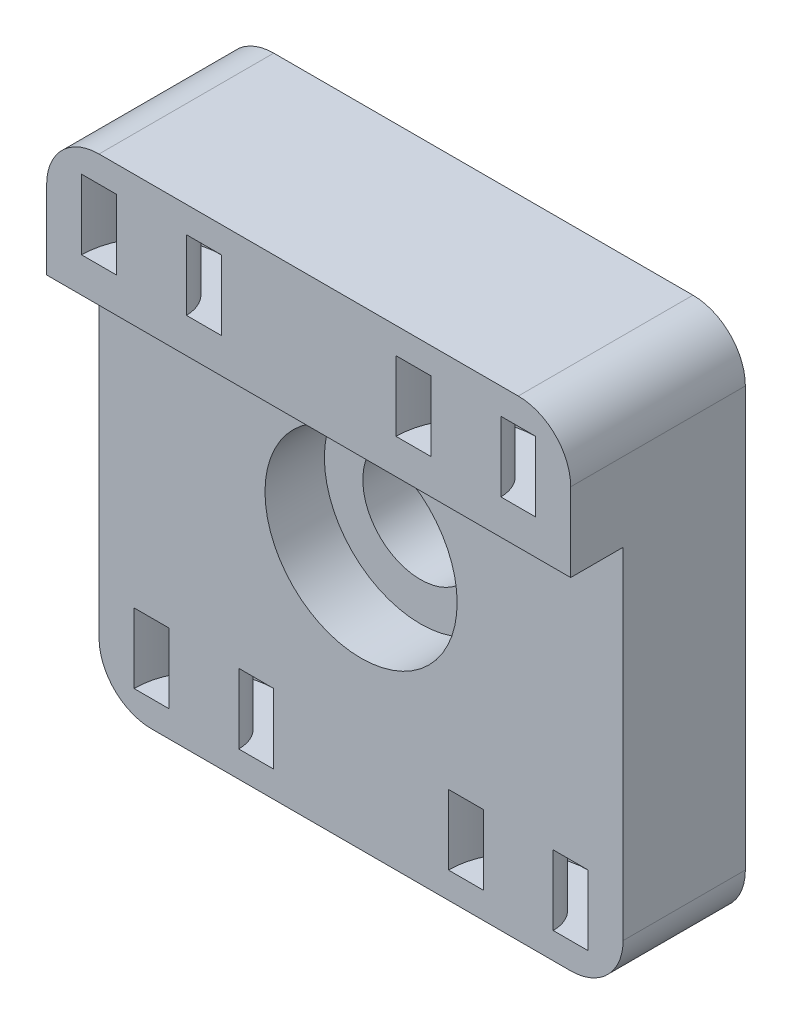
SolidWorks part; units mm, degrees
ref_plane "Přední rovina" through (0, 0, 0) normal (0, 0, 1) x (1, 0, 0)
ref_plane "Horní rovina" through (0, 0, 0) normal (0, 1, 0) x (1, 0, 0)
ref_plane "Pravá rovina" through (0, 0, 0) normal (1, 0, 0) x (0, 0, -1)
sketch "Base sketch" plane through (0, 0, 0) normal (0, 0, 1) x (1, 0, 0)
  line L1 (-15, 15) -> (15, 15)
  line L2 (-15, 15) -> (-15, -15)
  line L3 (-15, -15) -> (15, -15)
  line L4 (15, 15) -> (15, -15)
  line L5 (-15, 15) -> (15, -15) construction
  line L6 (-15, -15) -> (15, 15) construction
  point P0 (0, 0)
  dimension "D1" = 30
extrude "Base" add sketch "Base sketch" along normal blind 7
sketch "Higher adapter sketch" plane through (0, 0, 7) normal (0, 0, 1) x (1, 0, 0)
  line L0 (15, -15) -> (15, 15) construction
  line L1 (-15, 15) -> (15, 15)
  line L2 (-15, 15) -> (-15, 7.5)
  line L3 (-15, 7.5) -> (15, 7.5)
  line L4 (15, 15) -> (15, 7.5)
  dimension "D1" = 7.5
extrude "Higher adapter" add sketch "Higher adapter sketch" along normal blind 3
sketch "Mount screw sketch" plane through (0, 0, 7) normal (0, 0, 1) x (1, 0, 0)
  point P0 (0, 0)
hole_wizard "Mount screw" positions "Skica4" profile "Skica5" counterbore size "M6" standard "ISO" end condition up to next
sketch "Skica4" plane through (0, 0, 7) normal (0, 0, 1) x (1, 0, 0)
  point P0 (0, 0)
sketch "Skica5" plane through (0, 0, 7) normal (1, 0, 0) x (0, -1, 0)
  line L0 (0, 0) -> (0, 7)
  line L1 (0, 7) -> (3.3, 7)
  line L3 (3.3, 7) -> (3.3, 3.4)
  line L4 (3.3, 3.4) -> (5.5, 3.4)
  line L5 (5.5, 3.4) -> (5.5, 0)
  line L7 (5.5, 0) -> (0, 0)
  line L11 (0, -6.35) -> (0, 107.95) construction
  dimension "Průměr díry skrz" = 6.6
  dimension "Hloubka díry skrz" = 7
  dimension "Průměr válcového zahloubení" = 11
  dimension "Hloubka válcového zahloubení" = 3.4
ref_plane "Bottom ties plane" through (0, -13.5, 0) normal (0, -1, 0) x (-1, 0, 0)
sketch "Bottom ties sketch" plane through (0, -13.5, 0) normal (0, -1, 0) x (1, 0, 0)
  line L0 (-15, 7) -> (15, 7) construction
  line L3 (0, 0) -> (0, 7)
  line L4 (-15, 0) -> (15, 0) construction
  circle A0 centre (-9, 7) radius 2
  circle A1 centre (-9, 7) radius 4
  circle A2 centre (9, 7) radius 4
  circle A3 centre (9, 7) radius 2
  dimension "D1" = 4
  dimension "D2" = 8
  dimension "D3" = 6
extrude "Bottom ties" cut sketch "Bottom ties sketch" against normal blind 4 contours A1 | A0 | A2 | A3
ref_plane "Top ties plane" through (0, 13.5, 0) normal (0, 1, 0) x (1, 0, 0)
sketch "Top ties sketch" plane through (0, 13.5, 0) normal (0, 1, 0) x (1, 0, 0)
  line L0 (0, 0) -> (0, -10)
  line L1 (15, 0) -> (-15, 0) construction
  line L2 (15, -10) -> (-15, -10) construction
  circle A0 centre (-9, -10) radius 2
  circle A1 centre (-9, -10) radius 4
  circle A2 centre (9, -10) radius 2
  circle A3 centre (9, -10) radius 4
  dimension "D2" = 4
  dimension "D3" = 8
  dimension "D1" = 6
extrude "Top ties" cut sketch "Top ties sketch" against normal blind 4 contours A1 | A0 | A3 | A2
fillet "Rounding" radius 3 4 edges at (-15, -15, 3.5) (15, -15, 3.5) (15, 15, 5) (-15, 15, 5)
